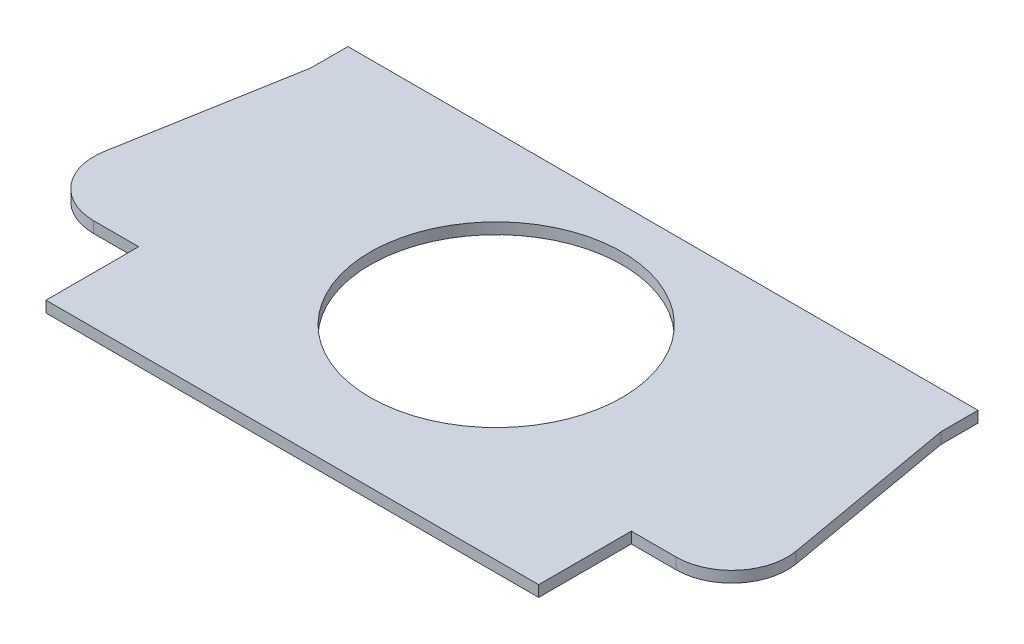
SolidWorks part; units mm, degrees
ref_plane "Front Plane" through (0, 0, 0) normal (0, 0, 1) x (1, 0, 0)
ref_plane "Top Plane" through (0, 0, 0) normal (0, 1, 0) x (1, 0, 0)
ref_plane "Right Plane" through (0, 0, 0) normal (1, 0, 0) x (0, 0, -1)
sketch "Sketch1" plane through (0, 0, 0) normal (0, 1, 0) x (1, 0, 0)
  line L0 (0, 212.4123) -> (0, -88.9614) construction
  line L1 (85, 90) -> (85, 100)
  line L2 (66.4613, 0) -> (66.4613, 25)
  line L3 (66.4613, 25) -> (96.4613, 25)
  line L4 (96.4613, 25) -> (96.4613, 105) construction
  line L5 (66.4613, 0) -> (-66.4613, 0)
  line L6 (85, 100) -> (-85, 100)
  line L7 (85, 90) -> (96.4613, 25)
  line L8 (-66.4613, 0) -> (-66.4613, 25)
  line L9 (-66.4613, 25) -> (-96.4613, 25)
  line L10 (-85, 90) -> (-96.4613, 25)
  line L11 (-85, 90) -> (-85, 100)
  point P12 (0, 0)
  point P16 (0, 100)
  dimension "D1" = 170
  dimension "D2" = 10
  dimension "D3" = 30
  dimension "D4" = 25
  dimension "D5" = 85
  dimension "D6" = 100
extrude "Boss-Extrude1" add sketch "Sketch1" along normal blind 3
sketch "Sketch2" plane through (0, 3, 0) normal (0, 1, 0) x (1, 0, 0)
  line L1 (0, 0) -> (0, 100) construction
  line L3 (-66.4613, 0) -> (66.4613, 0) construction
  line L4 (85, 100) -> (-85, 100) construction
  circle A0 centre (0, 55) radius 34
  dimension "D1" = 68
  dimension "D2" = 55
extrude "Cut-Extrude2" cut sketch "Sketch2" against normal blind 12
fillet "Fillet1" radius 15 2 edges at (-96.4613, 1.5, -25) (96.4613, 1.5, -25)
